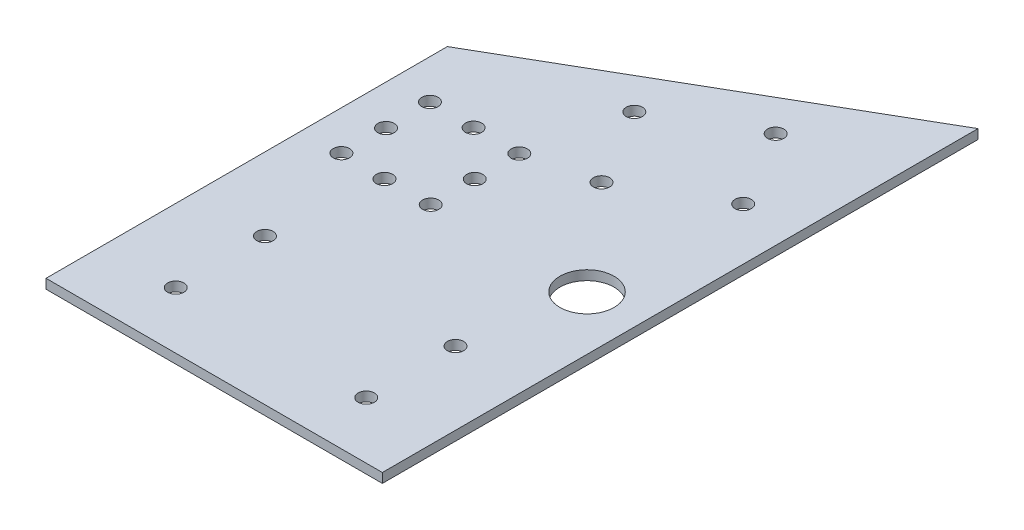
SolidWorks part; units mm, degrees
material "Plain Carbon Steel"
ref_plane "Front Plane" through (0, 0, 0) normal (0, 0, 1) x (1, 0, 0)
ref_plane "Top Plane" through (0, 0, 0) normal (0, 1, 0) x (1, 0, 0)
ref_plane "Right Plane" through (0, 0, 0) normal (1, 0, 0) x (0, 0, -1)
sketch "Sketch4" plane through (0, 0, 0) normal (0, 1, 0) x (1, 0, 0)
  line L3 (-36.7366, -50) -> (87.5, -50)
  line L4 (87.5, 0) -> (87.5, -50)
  line L7 (-36.7366, -50) -> (-36.7366, 23.5833)
  line L11 (87.5, 0) -> (87.5, 130)
  line L12 (-36.7366, 23.5833) -> (87.5, 23.5833) construction
  line L13 (25.3817, -50) -> (25.3817, 86.4601) construction
  line L14 (67.5, 86.4601) -> (67.5, -50) construction
  line L15 (-36.7366, 23.5833) -> (-36.7366, 58.2398)
  line L16 (-36.7366, 58.2398) -> (-36.7366, 98.2398)
  line L17 (87.5, 130) -> (87.5, 170)
  line L18 (87.5, 170) -> (-36.7366, 98.2398)
  circle A4 centre (67.5, 45.5833) radius 10
  point P0 (0, 0)
  dimension "D5" = 20
  dimension "D6" = 22
  dimension "D1" = 124.2366
  dimension "D2" = 73.5833
  dimension "D3" = 180
extrude "Boss-Extrude1" add sketch "Sketch4" along normal blind 3.5
hole_wizard "Ø6.0mm Dowel Hole3" positions "Sketch9" profile "Sketch10" hole size "Ø6.0" standard "ANSI Metric" end condition through all
sketch "Sketch9" plane through (-105.5979, -96.5, 23.6048) normal (0, -1, 0) x (-1, 0, 0)
  point P0 (-166.162, -5.4146)
sketch "Sketch10" plane through (60.5641, -96.5, 29.0194) normal (1, 0, 0) x (0, 0, -1)
  line L0 (0, 0) -> (0, 100)
  line L1 (0, 100) -> (3, 100)
  line L2 (3, 100) -> (3, 0)
  line L3 (3, 0) -> (0, 0)
  line L4 (0, -6.35) -> (0, 107.95) construction
  dimension "Thru Hole Dia." = 6
  dimension "Thru Hole Depth" = 100
hole_wizard "Ø6.0mm Dowel Hole4" positions "Sketch11" profile "Sketch12" hole size "Ø6.0" standard "ANSI Metric" end condition through all
sketch "Sketch11" plane through (-105.5979, 0, 23.6048) normal (0, -1, 0) x (-1, 0, 0)
  point P0 (-166.162, -5.4146)
sketch "Sketch12" plane through (60.5641, 0, 29.0194) normal (1, 0, 0) x (0, 0, -1)
  line L0 (0, 0) -> (0, 3.5)
  line L1 (0, 3.5) -> (3, 3.5)
  line L2 (3, 3.5) -> (3, 0)
  line L3 (3, 0) -> (0, 0)
  line L4 (0, -6.35) -> (0, 107.95) construction
  dimension "Thru Hole Dia." = 6
  dimension "Thru Hole Depth" = 3.5
hole_wizard "Ø6.0mm Dowel Hole5" positions "Sketch13" profile "Sketch14" hole size "Ø6.0" standard "ANSI Metric" end condition through all
sketch "Sketch13" plane through (-105.5979, -96.5, 23.6048) normal (0, -1, 0) x (-1, 0, 0)
  point P0 (-166.1755, 27.5457)
sketch "Sketch14" plane through (60.5776, -96.5, -3.9409) normal (1, 0, 0) x (0, 0, -1)
  line L0 (0, 0) -> (0, 100)
  line L1 (0, 100) -> (3, 100)
  line L2 (3, 100) -> (3, 0)
  line L3 (3, 0) -> (0, 0)
  line L4 (0, -6.35) -> (0, 107.95) construction
  dimension "Thru Hole Dia." = 6
  dimension "Thru Hole Depth" = 100
hole_wizard "Ø6.0mm Dowel Hole6" positions "Sketch15" profile "Sketch16" hole size "Ø6.0" standard "ANSI Metric" end condition through all
sketch "Sketch15" plane through (-105.5979, 0, 23.6048) normal (0, -1, 0) x (-1, 0, 0)
  point P0 (-166.1755, 27.5457)
sketch "Sketch16" plane through (60.5776, 0, -3.9409) normal (1, 0, 0) x (0, 0, -1)
  line L0 (0, 0) -> (0, 3.5)
  line L1 (0, 3.5) -> (3, 3.5)
  line L2 (3, 3.5) -> (3, 0)
  line L3 (3, 0) -> (0, 0)
  line L4 (0, -6.35) -> (0, 107.95) construction
  dimension "Thru Hole Dia." = 6
  dimension "Thru Hole Depth" = 3.5
hole_wizard "Ø6.0mm Dowel Hole7" positions "Sketch17" profile "Sketch18" hole size "Ø6.0" standard "ANSI Metric" end condition through all
sketch "Sketch17" plane through (-105.5979, -96.5, 23.6048) normal (0, -1, 0) x (-1, 0, 0)
  point P0 (-95.7972, 27.5475)
sketch "Sketch18" plane through (-9.8007, -96.5, -3.9427) normal (1, 0, 0) x (0, 0, -1)
  line L0 (0, 0) -> (0, 100)
  line L1 (0, 100) -> (3, 100)
  line L2 (3, 100) -> (3, 0)
  line L3 (3, 0) -> (0, 0)
  line L4 (0, -6.35) -> (0, 107.95) construction
  dimension "Thru Hole Dia." = 6
  dimension "Thru Hole Depth" = 100
hole_wizard "Ø6.0mm Dowel Hole8" positions "Sketch19" profile "Sketch20" hole size "Ø6.0" standard "ANSI Metric" end condition through all
sketch "Sketch19" plane through (-105.5979, 0, 23.6048) normal (0, -1, 0) x (-1, 0, 0)
  point P0 (-95.7972, 27.5475)
sketch "Sketch20" plane through (-9.8007, 0, -3.9427) normal (1, 0, 0) x (0, 0, -1)
  line L0 (0, 0) -> (0, 3.5)
  line L1 (0, 3.5) -> (3, 3.5)
  line L2 (3, 3.5) -> (3, 0)
  line L3 (3, 0) -> (0, 0)
  line L4 (0, -6.35) -> (0, 107.95) construction
  dimension "Thru Hole Dia." = 6
  dimension "Thru Hole Depth" = 3.5
hole_wizard "Ø6.0mm Dowel Hole9" positions "Sketch21" profile "Sketch22" hole size "Ø6.0" standard "ANSI Metric" end condition through all
sketch "Sketch21" plane through (-105.5979, -96.5, 23.6048) normal (0, -1, 0) x (-1, 0, 0)
  point P0 (-83.3613, 100.9147)
sketch "Sketch22" plane through (-22.2366, -96.5, -77.31) normal (1, 0, 0) x (0, 0, -1)
  line L0 (0, 0) -> (0, 100)
  line L1 (0, 100) -> (3, 100)
  line L2 (3, 100) -> (3, 0)
  line L3 (3, 0) -> (0, 0)
  line L4 (0, -6.35) -> (0, 107.95) construction
  dimension "Thru Hole Dia." = 6
  dimension "Thru Hole Depth" = 100
hole_wizard "Ø6.0mm Dowel Hole10" positions "Sketch23" profile "Sketch24" hole size "Ø6.0" standard "ANSI Metric" end condition through all
sketch "Sketch23" plane through (-105.5979, 0, 23.6048) normal (0, -1, 0) x (-1, 0, 0)
  point P0 (-83.3613, 100.9147)
sketch "Sketch24" plane through (-22.2366, 0, -77.31) normal (1, 0, 0) x (0, 0, -1)
  line L0 (0, 0) -> (0, 3.5)
  line L1 (0, 3.5) -> (3, 3.5)
  line L2 (3, 3.5) -> (3, 0)
  line L3 (3, 0) -> (0, 0)
  line L4 (0, -6.35) -> (0, 107.95) construction
  dimension "Thru Hole Dia." = 6
  dimension "Thru Hole Depth" = 3.5
hole_wizard "Ø6.0mm Dowel Hole11" positions "Sketch25" profile "Sketch26" hole size "Ø6.0" standard "ANSI Metric" end condition through all
sketch "Sketch25" plane through (-105.5979, -96.5, 23.6048) normal (0, -1, 0) x (-1, 0, 0)
  point P0 (-116.3613, 100.9147)
sketch "Sketch26" plane through (10.7634, -96.5, -77.31) normal (1, 0, 0) x (0, 0, -1)
  line L0 (0, 0) -> (0, 100)
  line L1 (0, 100) -> (3, 100)
  line L2 (3, 100) -> (3, 0)
  line L3 (3, 0) -> (0, 0)
  line L4 (0, -6.35) -> (0, 107.95) construction
  dimension "Thru Hole Dia." = 6
  dimension "Thru Hole Depth" = 100
hole_wizard "Ø6.0mm Dowel Hole12" positions "Sketch27" profile "Sketch28" hole size "Ø6.0" standard "ANSI Metric" end condition through all
sketch "Sketch27" plane through (-105.5979, 0, 23.6048) normal (0, -1, 0) x (-1, 0, 0)
  point P0 (-116.3613, 100.9147)
sketch "Sketch28" plane through (10.7634, 0, -77.31) normal (1, 0, 0) x (0, 0, -1)
  line L0 (0, 0) -> (0, 3.5)
  line L1 (0, 3.5) -> (3, 3.5)
  line L2 (3, 3.5) -> (3, 0)
  line L3 (3, 0) -> (0, 0)
  line L4 (0, -6.35) -> (0, 107.95) construction
  dimension "Thru Hole Dia." = 6
  dimension "Thru Hole Depth" = 3.5
hole_wizard "Ø6.0mm Dowel Hole13" positions "Sketch29" profile "Sketch30" hole size "Ø6.0" standard "ANSI Metric" end condition through all
sketch "Sketch29" plane through (-105.5979, -96.5, 23.6048) normal (0, -1, 0) x (-1, 0, 0)
  point P0 (-116.3613, 68.1913)
sketch "Sketch30" plane through (10.7634, -96.5, -44.5866) normal (1, 0, 0) x (0, 0, -1)
  line L0 (0, 0) -> (0, 100)
  line L1 (0, 100) -> (3, 100)
  line L2 (3, 100) -> (3, 0)
  line L3 (3, 0) -> (0, 0)
  line L4 (0, -6.35) -> (0, 107.95) construction
  dimension "Thru Hole Dia." = 6
  dimension "Thru Hole Depth" = 100
hole_wizard "Ø6.0mm Dowel Hole14" positions "Sketch31" profile "Sketch32" hole size "Ø6.0" standard "ANSI Metric" end condition through all
sketch "Sketch31" plane through (-105.5979, 0, 23.6048) normal (0, -1, 0) x (-1, 0, 0)
  point P0 (-116.3613, 68.1913)
sketch "Sketch32" plane through (10.7634, 0, -44.5866) normal (1, 0, 0) x (0, 0, -1)
  line L0 (0, 0) -> (0, 3.5)
  line L1 (0, 3.5) -> (3, 3.5)
  line L2 (3, 3.5) -> (3, 0)
  line L3 (3, 0) -> (0, 0)
  line L4 (0, -6.35) -> (0, 107.95) construction
  dimension "Thru Hole Dia." = 6
  dimension "Thru Hole Depth" = 3.5
hole_wizard "Ø6.0mm Dowel Hole15" positions "Sketch33" profile "Sketch34" hole size "Ø6.0" standard "ANSI Metric" end condition through all
sketch "Sketch33" plane through (-105.5979, -96.5, 23.6048) normal (0, -1, 0) x (-1, 0, 0)
  point P0 (-83.4014, 68.1778)
sketch "Sketch34" plane through (-22.1965, -96.5, -44.5731) normal (1, 0, 0) x (0, 0, -1)
  line L0 (0, 0) -> (0, 100)
  line L1 (0, 100) -> (3, 100)
  line L2 (3, 100) -> (3, 0)
  line L3 (3, 0) -> (0, 0)
  line L4 (0, -6.35) -> (0, 107.95) construction
  dimension "Thru Hole Dia." = 6
  dimension "Thru Hole Depth" = 100
hole_wizard "Ø6.0mm Dowel Hole16" positions "Sketch35" profile "Sketch36" hole size "Ø6.0" standard "ANSI Metric" end condition through all
sketch "Sketch35" plane through (-105.5979, 0, 23.6048) normal (0, -1, 0) x (-1, 0, 0)
  point P0 (-83.4014, 68.1778)
sketch "Sketch36" plane through (-22.1965, 0, -44.5731) normal (1, 0, 0) x (0, 0, -1)
  line L0 (0, 0) -> (0, 3.5)
  line L1 (0, 3.5) -> (3, 3.5)
  line L2 (3, 3.5) -> (3, 0)
  line L3 (3, 0) -> (0, 0)
  line L4 (0, -6.35) -> (0, 107.95) construction
  dimension "Thru Hole Dia." = 6
  dimension "Thru Hole Depth" = 3.5
hole_wizard "Ø6.0mm Dowel Hole17" positions "Sketch37" profile "Sketch38" hole size "Ø6.0" standard "ANSI Metric"
sketch "Sketch37" plane through (-105.5979, 3.5, 23.6048) normal (0, 1, 0) x (1, 0, 0)
  point P0 (83.6143, 84.4398)
sketch "Sketch38" plane through (-21.9836, 3.5, -60.8351) normal (1, 0, 0) x (0, 0, 1)
  line L0 (0, 0) -> (0, 32.4426)
  line L1 (0, 32.4426) -> (3, 30.64)
  line L2 (3, 30.64) -> (3, 0)
  line L3 (3, 0) -> (0, 0)
  line L4 (0, 32.4426) -> (-3, 30.64) construction
  line L5 (0, -6.35) -> (0, 107.95) construction
  dimension "Hole Dia." = 6
  dimension "Hole Depth" = 30.64
  dimension "Drill Angle" = 118
hole_wizard "Ø6.0mm Dowel Hole18" positions "Sketch39" profile "Sketch40" hole size "Ø6.0" standard "ANSI Metric"
sketch "Sketch39" plane through (-105.5979, 3.5, 23.6048) normal (0, 1, 0) x (1, 0, 0)
  point P0 (116.2944, 84.5278)
sketch "Sketch40" plane through (10.6965, 3.5, -60.923) normal (1, 0, 0) x (0, 0, 1)
  line L0 (0, 0) -> (0, 32.4426)
  line L1 (0, 32.4426) -> (3, 30.64)
  line L2 (3, 30.64) -> (3, 0)
  line L3 (3, 0) -> (0, 0)
  line L4 (0, 32.4426) -> (-3, 30.64) construction
  line L5 (0, -6.35) -> (0, 107.95) construction
  dimension "Hole Dia." = 6
  dimension "Hole Depth" = 30.64
  dimension "Drill Angle" = 118
hole_wizard "Ø6.0mm Dowel Hole19" positions "Sketch41" profile "Sketch42" hole size "Ø6.0" standard "ANSI Metric"
sketch "Sketch41" plane through (-105.5979, 3.5, 23.6048) normal (0, 1, 0) x (1, 0, 0)
  point P0 (99.6023, 67.8828)
sketch "Sketch42" plane through (-5.9956, 3.5, -44.2781) normal (1, 0, 0) x (0, 0, 1)
  line L0 (0, 0) -> (0, 32.4426)
  line L1 (0, 32.4426) -> (3, 30.64)
  line L2 (3, 30.64) -> (3, 0)
  line L3 (3, 0) -> (0, 0)
  line L4 (0, 32.4426) -> (-3, 30.64) construction
  line L5 (0, -6.35) -> (0, 107.95) construction
  dimension "Hole Dia." = 6
  dimension "Hole Depth" = 30.64
  dimension "Drill Angle" = 118
hole_wizard "Ø6.0mm Dowel Hole20" positions "Sketch43" profile "Sketch44" hole size "Ø6.0" standard "ANSI Metric"
sketch "Sketch43" plane through (-105.5979, 3.5, 23.6048) normal (0, 1, 0) x (1, 0, 0)
  point P0 (99.6586, 100.7377)
sketch "Sketch44" plane through (-5.9393, 3.5, -77.1329) normal (1, 0, 0) x (0, 0, 1)
  line L0 (0, 0) -> (0, 32.4426)
  line L1 (0, 32.4426) -> (3, 30.64)
  line L2 (3, 30.64) -> (3, 0)
  line L3 (3, 0) -> (0, 0)
  line L4 (0, 32.4426) -> (-3, 30.64) construction
  line L5 (0, -6.35) -> (0, 107.95) construction
  dimension "Hole Dia." = 6
  dimension "Hole Depth" = 30.64
  dimension "Drill Angle" = 118
hole_wizard "Ø6.0mm Dowel Hole21" positions "Sketch45" profile "Sketch46" hole size "Ø6.0" standard "AS" end condition through all
sketch "Sketch45" plane through (-105.5979, -96.5, 23.6048) normal (0, -1, 0) x (-1, 0, 0)
  point P0 (-173.8582, 126.1225)
sketch "Sketch46" plane through (68.2603, -96.5, -102.5178) normal (1, 0, 0) x (0, 0, -1)
  line L0 (0, 0) -> (0, 100)
  line L1 (0, 100) -> (3, 100)
  line L2 (3, 100) -> (3, 0)
  line L3 (3, 0) -> (0, 0)
  line L4 (0, -6.35) -> (0, 107.95) construction
  dimension "Thru Hole Dia." = 6
  dimension "Thru Hole Depth" = 100
hole_wizard "Ø6.0mm Dowel Hole22" positions "Sketch47" profile "Sketch48" hole size "Ø6.0" standard "AS" end condition through all
sketch "Sketch47" plane through (-105.5979, 0, 23.6048) normal (0, -1, 0) x (-1, 0, 0)
  point P0 (-173.8582, 126.1225)
sketch "Sketch48" plane through (68.2603, 0, -102.5178) normal (1, 0, 0) x (0, 0, -1)
  line L0 (0, 0) -> (0, 3.5)
  line L1 (0, 3.5) -> (3, 3.5)
  line L2 (3, 3.5) -> (3, 0)
  line L3 (3, 0) -> (0, 0)
  line L4 (0, -6.35) -> (0, 107.95) construction
  dimension "Thru Hole Dia." = 6
  dimension "Thru Hole Depth" = 3.5
hole_wizard "Ø6.0mm Dowel Hole23" positions "Sketch49" profile "Sketch50" hole size "Ø6.0" standard "AS" end condition through all
sketch "Sketch49" plane through (-105.5979, -96.5, 23.6048) normal (0, -1, 0) x (-1, 0, 0)
  point P0 (-157.3708, 154.6039)
sketch "Sketch50" plane through (51.7729, -96.5, -130.9991) normal (1, 0, 0) x (0, 0, -1)
  line L0 (0, 0) -> (0, 100)
  line L1 (0, 100) -> (3, 100)
  line L2 (3, 100) -> (3, 0)
  line L3 (3, 0) -> (0, 0)
  line L4 (0, -6.35) -> (0, 107.95) construction
  dimension "Thru Hole Dia." = 6
  dimension "Thru Hole Depth" = 100
hole_wizard "Ø6.0mm Dowel Hole24" positions "Sketch51" profile "Sketch52" hole size "Ø6.0" standard "AS" end condition through all
sketch "Sketch51" plane through (-105.5979, 0, 23.6048) normal (0, -1, 0) x (-1, 0, 0)
  point P0 (-157.3708, 154.6039)
sketch "Sketch52" plane through (51.7729, 0, -130.9991) normal (1, 0, 0) x (0, 0, -1)
  line L0 (0, 0) -> (0, 3.5)
  line L1 (0, 3.5) -> (3, 3.5)
  line L2 (3, 3.5) -> (3, 0)
  line L3 (3, 0) -> (0, 0)
  line L4 (0, -6.35) -> (0, 107.95) construction
  dimension "Thru Hole Dia." = 6
  dimension "Thru Hole Depth" = 3.5
hole_wizard "Ø6.0mm Dowel Hole25" positions "Sketch53" profile "Sketch54" hole size "Ø6.0" standard "AS" end condition through all
sketch "Sketch53" plane through (-105.5979, -96.5, 23.6048) normal (0, -1, 0) x (-1, 0, 0)
  point P0 (-124.2873, 135.4746)
sketch "Sketch54" plane through (18.6894, -96.5, -111.8698) normal (1, 0, 0) x (0, 0, -1)
  line L0 (0, 0) -> (0, 100)
  line L1 (0, 100) -> (3, 100)
  line L2 (3, 100) -> (3, 0)
  line L3 (3, 0) -> (0, 0)
  line L4 (0, -6.35) -> (0, 107.95) construction
  dimension "Thru Hole Dia." = 6
  dimension "Thru Hole Depth" = 100
hole_wizard "Ø6.0mm Dowel Hole26" positions "Sketch55" profile "Sketch56" hole size "Ø6.0" standard "AS" end condition through all
sketch "Sketch55" plane through (-105.5979, 0, 23.6048) normal (0, -1, 0) x (-1, 0, 0)
  point P0 (-124.2873, 135.4746)
sketch "Sketch56" plane through (18.6894, 0, -111.8698) normal (1, 0, 0) x (0, 0, -1)
  line L0 (0, 0) -> (0, 3.5)
  line L1 (0, 3.5) -> (3, 3.5)
  line L2 (3, 3.5) -> (3, 0)
  line L3 (3, 0) -> (0, 0)
  line L4 (0, -6.35) -> (0, 107.95) construction
  dimension "Thru Hole Dia." = 6
  dimension "Thru Hole Depth" = 3.5
hole_wizard "Ø6.0mm Dowel Hole27" positions "Sketch57" profile "Sketch58" hole size "Ø6.0" standard "AS" end condition through all
sketch "Sketch57" plane through (-105.5979, -96.5, 23.6048) normal (0, -1, 0) x (-1, 0, 0)
  point P0 (-140.7643, 106.8901)
sketch "Sketch58" plane through (35.1663, -96.5, -83.2853) normal (1, 0, 0) x (0, 0, -1)
  line L0 (0, 0) -> (0, 100)
  line L1 (0, 100) -> (3, 100)
  line L2 (3, 100) -> (3, 0)
  line L3 (3, 0) -> (0, 0)
  line L4 (0, -6.35) -> (0, 107.95) construction
  dimension "Thru Hole Dia." = 6
  dimension "Thru Hole Depth" = 100
hole_wizard "Ø6.0mm Dowel Hole28" positions "Sketch59" profile "Sketch60" hole size "Ø6.0" standard "AS" end condition through all
sketch "Sketch59" plane through (-105.5979, 0, 23.6048) normal (0, -1, 0) x (-1, 0, 0)
  point P0 (-140.7643, 106.8901)
sketch "Sketch60" plane through (35.1663, 0, -83.2853) normal (1, 0, 0) x (0, 0, -1)
  line L0 (0, 0) -> (0, 3.5)
  line L1 (0, 3.5) -> (3, 3.5)
  line L2 (3, 3.5) -> (3, 0)
  line L3 (3, 0) -> (0, 0)
  line L4 (0, -6.35) -> (0, 107.95) construction
  dimension "Thru Hole Dia." = 6
  dimension "Thru Hole Depth" = 3.5
hole_wizard "Ø6.0mm Dowel Hole29" positions "Sketch61" profile "Sketch62" hole size "Ø6.0" standard "ANSI Metric" end condition through all
sketch "Sketch61" plane through (-105.5979, -96.5, 23.6048) normal (0, -1, 0) x (-1, 0, 0)
  point P0 (-95.7972, -5.4146)
sketch "Sketch62" plane through (-9.8007, -96.5, 29.0194) normal (1, 0, 0) x (0, 0, -1)
  line L0 (0, 0) -> (0, 100)
  line L1 (0, 100) -> (3, 100)
  line L2 (3, 100) -> (3, 0)
  line L3 (3, 0) -> (0, 0)
  line L4 (0, -6.35) -> (0, 107.95) construction
  dimension "Thru Hole Dia." = 6
  dimension "Thru Hole Depth" = 100
hole_wizard "Ø6.0mm Dowel Hole30" positions "Sketch63" profile "Sketch64" hole size "Ø6.0" standard "ANSI Metric" end condition through all
sketch "Sketch63" plane through (-105.5979, 0, 23.6048) normal (0, -1, 0) x (-1, 0, 0)
  point P0 (-95.7972, -5.4146)
sketch "Sketch64" plane through (-9.8007, 0, 29.0194) normal (1, 0, 0) x (0, 0, -1)
  line L0 (0, 0) -> (0, 3.5)
  line L1 (0, 3.5) -> (3, 3.5)
  line L2 (3, 3.5) -> (3, 0)
  line L3 (3, 0) -> (0, 0)
  line L4 (0, -6.35) -> (0, 107.95) construction
  dimension "Thru Hole Dia." = 6
  dimension "Thru Hole Depth" = 3.5
